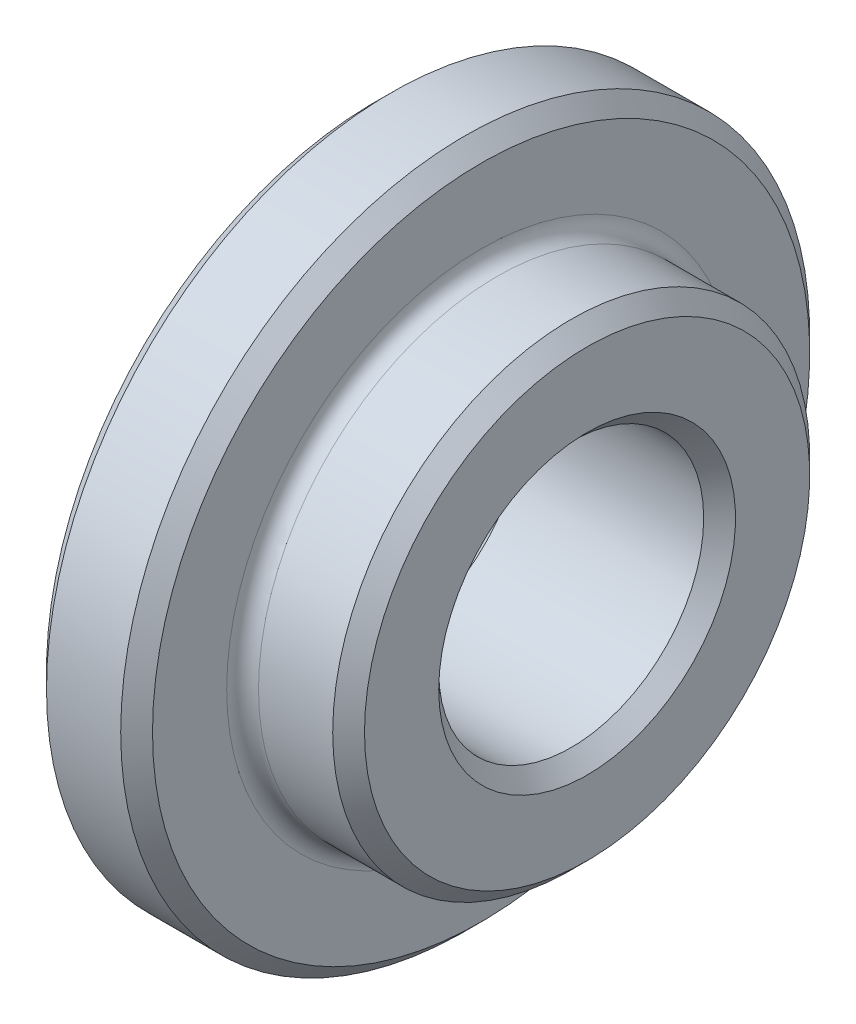
SolidWorks part; units mm, degrees
ref_plane "Přední rovina" through (0, 0, 0) normal (0, 0, 1) x (1, 0, 0)
ref_plane "Vrchní rovina" through (0, 0, 0) normal (0, 1, 0) x (1, 0, 0)
ref_plane "Pravá rovina" through (0, 0, 0) normal (1, 0, 0) x (0, 0, -1)
sketch "Skica1" plane through (0, 0, 0) normal (0, 0, 1) x (1, 0, 0)
  line L0 (0, 2.5) -> (4, 2.5)
  line L1 (4, 2.5) -> (4, 4.5)
  line L2 (4, 4.5) -> (2, 4.5)
  line L3 (2, 4.5) -> (2, 6.5)
  line L4 (2, 6.5) -> (0, 6.5)
  line L5 (0, 6.5) -> (0, 2.5)
  line L6 (0, 0) -> (4, 0) construction
  dimension "D1" = 13
  dimension "d_" = 5
  dimension "L" = 4
  dimension "D" = 9
  dimension "b" = 2
revolve "Otočit kolem osy1" add sketch "Skica1" angle 360 about L6
fillet "Zaoblit1" radius 0.3 1 edges at (2, 0, 4.5)
chamfer "Zkosit1" distance 0.3 angle 45 5 edges at (0, 0, 6.5) (2, 0, 6.5) (4, 0, 4.5) (4, 0, 2.5) (0, 0, 2.5)
